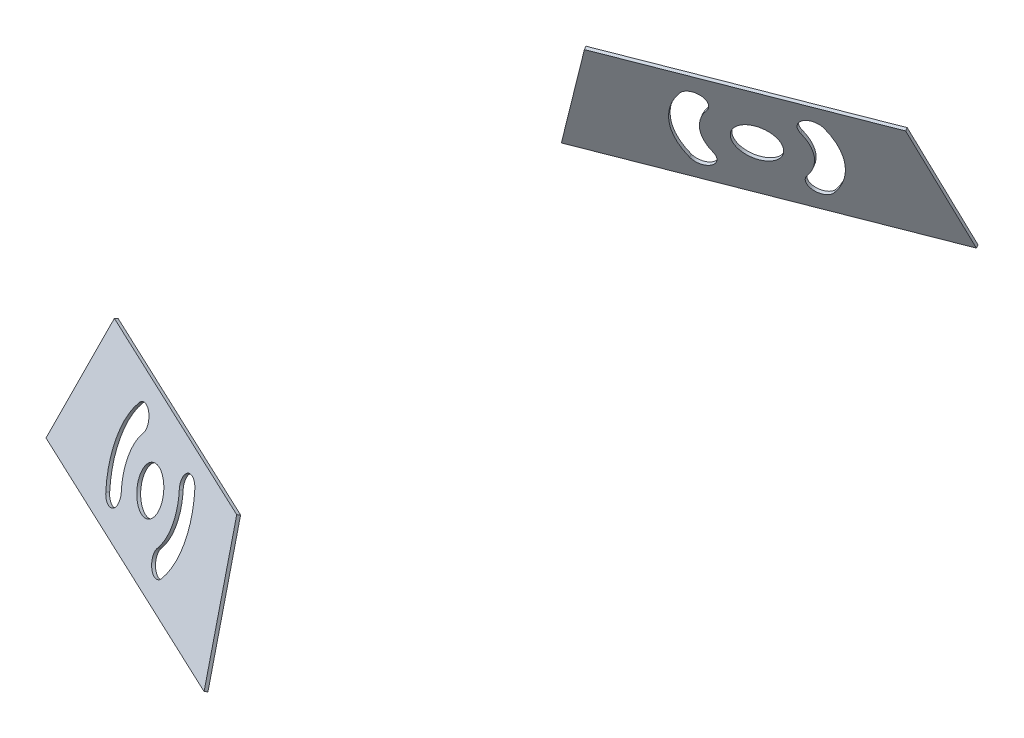
SolidWorks part; units mm, degrees
material "AISI 4130 Steel, normalized at 870C"
ref_plane "Front Plane" through (0, 0, 0) normal (0, 0, 1) x (1, 0, 0)
ref_plane "Top Plane" through (0, 0, 0) normal (0, 1, 0) x (1, 0, 0)
ref_plane "Right Plane" through (0, 0, 0) normal (1, 0, 0) x (0, 0, -1)
sketch3d "3DSketch1"
  line L3 (-454.5752, 354.5254, -240.5006) -> (-149.3117, 1123.0514, -89.0577) construction
  line L4 (-116.5201, 920.6306, -177.9421) -> (-227.8509, 925.3226, -128.0214) construction
  line L5 (-73.974, 657.9958, -293.267) -> (-149.3117, 1123.0514, -89.0577) construction
ref_plane "Plane1" through (-185.788, 158.377, -429.2212) normal (0.3762, -0.3207, 0.8692) x (0.9258, 0.1669, -0.3391)
sketch "Sketch2" plane through (-185.788, 158.377, -429.2212) normal (0.3762, -0.3207, 0.8692) x (0.9258, 0.1669, -0.3391)
  line L0 (113.7183, 735.7925) -> (-39.2229, 769.6336)
  line L1 (-39.2229, 769.6336) -> (-73.8842, 696.377)
  line L2 (-280.1015, 260.5366) -> (79.4523, 1020.4537) construction
  line L3 (-73.8842, 696.377) -> (123.7262, 652.6519)
  line L4 (140.8183, 510.6614) -> (79.4523, 1020.4537) construction
  line L5 (123.7262, 652.6519) -> (113.7183, 735.7925)
  line L6 (37.2477, 752.713) -> (24.921, 674.5144) construction
  line L7 (-56.5535, 733.0053) -> (118.7222, 694.2222) construction
  line L8 (106.1626, 798.5607) -> (-13.0548, 824.9398) construction
  line L9 (140.8183, 510.6614) -> (74.7475, 1059.539) construction
  circle A0 centre (31.0843, 713.6137) radius 13
  dimension "D1" = 26
extrude "Boss-Extrude1" add sketch "Sketch2" against normal blind 2 from offset 12.7 offset against normal yes
sketch "Sketch3" plane through (-191.3189, 163.0918, -441.9989) normal (-0.3762, 0.3207, -0.8692) x (-0.9258, -0.1669, 0.3391)
  line L0 (-31.0843, 713.6137) -> (1.5408, 699.6192) construction
  line L1 (-31.0843, 713.6137) -> (3.6676, 720.8631) construction
  line L2 (-31.0843, 713.6137) -> (-55.3934, 687.7425) construction
  line L3 (-31.0843, 713.6137) -> (-65.8363, 706.3644) construction
  arc A0 (-55.3934, 687.7425) -> (-63.7095, 727.6083) centre (-31.0843, 713.6137) cw construction
  arc A1 (-70.6022, 730.5649) -> (-60.5291, 682.2768) centre (-31.0843, 713.6137) ccw
  arc A2 (-56.8169, 724.6517) -> (-50.2577, 693.2083) centre (-31.0843, 713.6137) ccw
  arc A3 (-56.8169, 724.6517) -> (-70.6022, 730.5649) centre (-63.7095, 727.6083) ccw
  arc A4 (-60.5291, 682.2768) -> (-50.2577, 693.2083) centre (-55.3934, 687.7425) ccw
  arc A5 (1.5408, 699.6192) -> (-6.7753, 739.4849) centre (-31.0843, 713.6137) ccw construction
  arc A6 (8.4335, 696.6626) -> (-1.6396, 744.9507) centre (-31.0843, 713.6137) ccw
  arc A7 (-5.3518, 702.5758) -> (-11.911, 734.0192) centre (-31.0843, 713.6137) ccw
  arc A8 (-5.3518, 702.5758) -> (8.4335, 696.6626) centre (1.5408, 699.6192) ccw
  arc A9 (-1.6396, 744.9507) -> (-11.911, 734.0192) centre (-6.7753, 739.4849) ccw
  circle A10 centre (-31.0843, 713.6137) radius 13 construction
  point P4 (-65.8363, 706.3644)
  point P9 (3.6676, 720.8631)
  dimension "D1" = 15
  dimension "D2" = 15
  dimension "D3" = 35
  dimension "D4" = 35
extrude "Cut-Extrude1" cut sketch "Sketch3" against normal blind 10
mirror "Mirror1" about plane through (0, 0, 0) normal (0, 0, 1) of bodies 103 101
